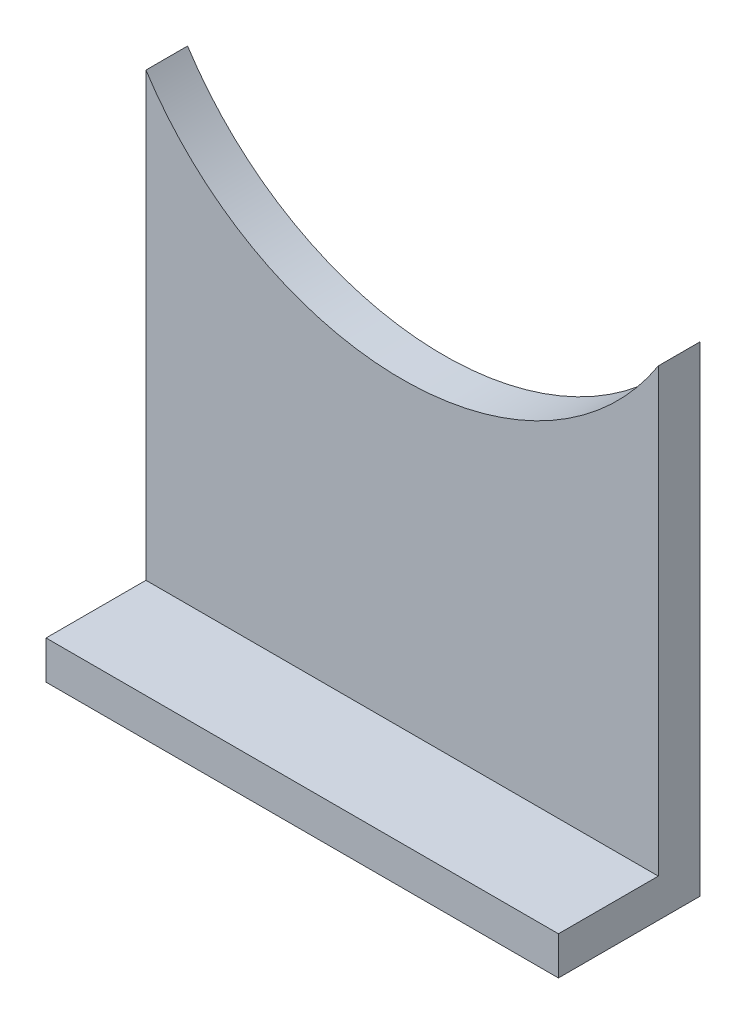
SolidWorks part; units mm, degrees
material "AISI 304"
ref_plane "Front" through (0, 0, 0) normal (0, 0, 1) x (1, 0, 0)
ref_plane "Top" through (0, 0, 0) normal (0, 1, 0) x (1, 0, 0)
ref_plane "Right" through (0, 0, 0) normal (1, 0, 0) x (0, 0, -1)
other "Configuration Table"
sketch "Sketch2" plane through (0, 0, 0) normal (0, 0, 1) x (1, 0, 0)
  line L1 (390.8614, -251.5651) -> (390.8614, -984.1524)
  line L2 (390.8614, -984.1524) -> (-390.8614, -984.1524)
  line L3 (-390.8614, -984.1524) -> (-390.8614, -251.5651)
  arc A0 (-390.8614, -251.5651) -> (390.8614, -251.5651) centre (0, 0) ccw
extrude "Boss-Extrude1" add sketch "Sketch2" along normal blind 63.5
sketch "Sketch3" plane through (0, 0, 63.5) normal (0, 0, 1) x (1, 0, 0)
  line L0 (390.8614, -984.1524) -> (390.8614, -251.5651) construction
  line L1 (-390.8614, -984.1524) -> (390.8614, -984.1524)
  line L2 (-390.8614, -984.1524) -> (-390.8614, -925.7324)
  line L3 (-390.8614, -925.7324) -> (390.8614, -925.7324)
  line L4 (390.8614, -984.1524) -> (390.8614, -925.7324)
  dimension "D1" = 58.42
extrude "Boss-Extrude2" add sketch "Sketch3" along normal blind 152.4
